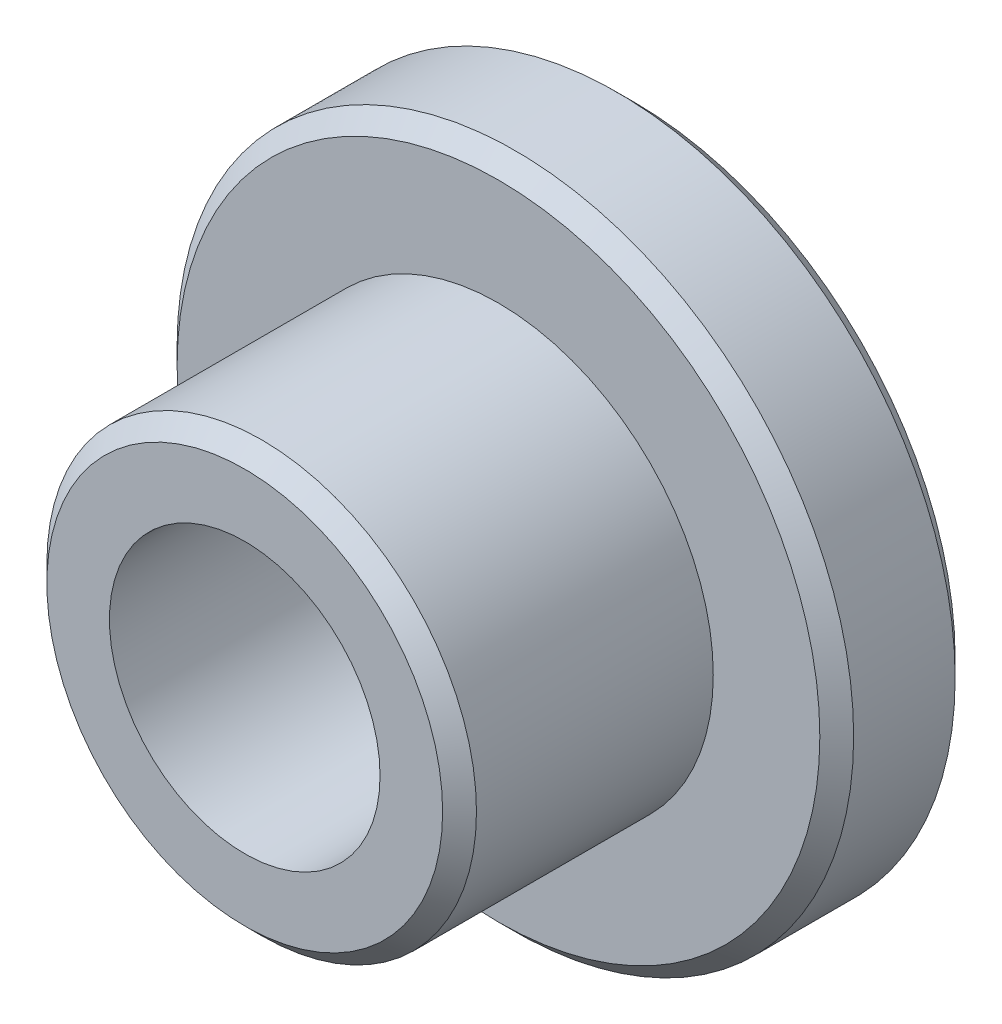
SolidWorks part; units mm, degrees
material "Latão com alto teor de chumbo, UNS C34200"
ref_plane "Plano frontal" through (0, 0, 0) normal (0, 0, 1) x (1, 0, 0)
ref_plane "Plano superior" through (0, 0, 0) normal (0, 1, 0) x (1, 0, 0)
ref_plane "Plano direito" through (0, 0, 0) normal (1, 0, 0) x (0, 0, -1)
sketch "Esboço1" plane through (0, 0, 0) normal (0, 0, 1) x (1, 0, 0)
  circle A0 centre (0, 0) radius 20
  dimension "D1" = 40
extrude "Ressalto-extrusão1" add sketch "Esboço1" along normal blind 8
sketch "Esboço2" plane through (0, 0, 8) normal (0, 0, 1) x (1, 0, 0)
  circle A0 centre (0, 0) radius 12.7
  dimension "D1" = 25.4
extrude "Ressalto-extrusão2" add sketch "Esboço2" along normal blind 15
chamfer "Chanfro1" distance 1 angle 45 1 edges at (12.7, 0, 23)
sketch "Esboço3" plane through (0, 0, 23) normal (0, 0, 1) x (1, 0, 0)
  circle A0 centre (0, 0) radius 8
  dimension "D1" = 16
extrude "Corte-extrusão1" cut sketch "Esboço3" against normal blind 15
sketch "Esboço4" plane through (0, 0, 0) normal (0, 0, -1) x (-1, 0, 0)
  circle A0 centre (0, 0) radius 6
  dimension "D1" = 12
extrude "Corte-extrusão2" cut sketch "Esboço4" against normal through all
chamfer "Chanfro2" distance 1 angle 45 2 edges at (20, 0, 8) (20, 0, 0)
